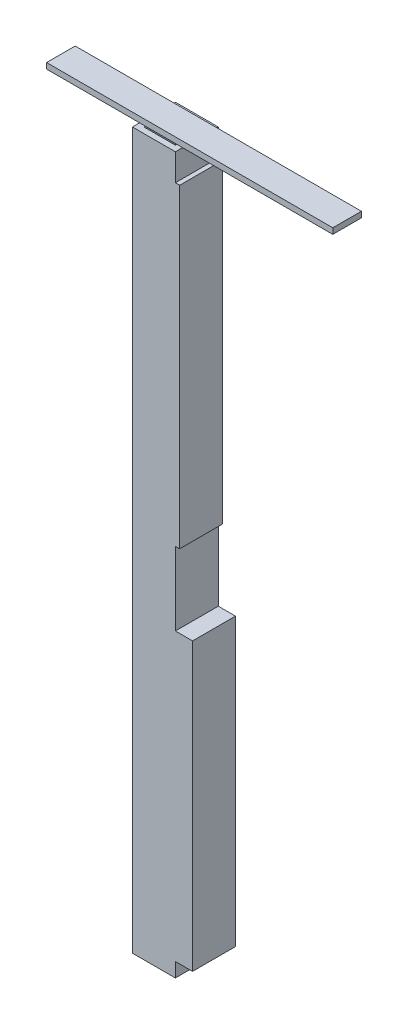
SolidWorks part; units mm, degrees
ref_plane "Front Plane" through (0, 0, 0) normal (0, 0, 1) x (1, 0, 0)
ref_plane "Top Plane" through (0, 0, 0) normal (0, 1, 0) x (1, 0, 0)
ref_plane "Right Plane" through (0, 0, 0) normal (1, 0, 0) x (0, 0, -1)
sketch "Sketch1" plane through (0, 0, 0) normal (0, 1, 0) x (1, 0, 0)
  line L1 (-15, 15) -> (15, 15)
  line L2 (-15, 15) -> (-15, -15)
  line L3 (-15, -15) -> (15, -15)
  line L4 (15, 15) -> (15, -15)
  dimension "D1" = 30
  dimension "D2" = 30
  dimension "D3" = 15
  dimension "D4" = 15
extrude "Extrude1" add sketch "Sketch1" along normal blind 500
sketch "Sketch2" plane through (0, 500, 0) normal (0, 1, 0) x (1, 0, 0)
  line L0 (15, 15) -> (-15, 15) construction
  line L1 (-11, 11) -> (11, 11)
  line L2 (-11, 11) -> (-11, -11)
  line L3 (-11, -11) -> (11, -11)
  line L4 (11, 11) -> (11, -11)
  line L5 (15, -15) -> (15, 15) construction
  line L6 (-15, -15) -> (15, -15) construction
  line L7 (-15, 15) -> (-15, -15) construction
  dimension "D1" = 4
  dimension "D2" = 4
  dimension "D3" = 4
  dimension "D4" = 4
extrude "Cut-Extrude1" cut sketch "Sketch2" against normal blind 500
sketch "Sketch3" plane through (0, 500, 0) normal (0, 1, 0) x (1, 0, 0)
  line L1 (-80, 10) -> (120, 10)
  line L2 (-80, 10) -> (-80, -10)
  line L3 (-80, -10) -> (120, -10)
  line L4 (120, 10) -> (120, -10)
  dimension "D1" = 20
  dimension "D2" = 10
  dimension "D3" = 80
  dimension "D4" = 120
extrude "Extrude2" add sketch "Sketch3" along normal blind 4
sketch "Sketch4" plane through (15, 0, 0) normal (1, 0, 0) x (0, 0, -1)
  line L0 (-15, 500) -> (-15, 0) construction
  line L1 (-15, 210) -> (15, 210)
  line L2 (-15, 210) -> (-15, 10)
  line L3 (-15, 10) -> (15, 10)
  line L4 (15, 210) -> (15, 10)
  line L5 (15, 500) -> (15, 0) construction
  line L6 (-15, 0) -> (15, 0) construction
  dimension "D1" = 200
  dimension "D2" = 30
  dimension "D3" = 10
extrude "Extrude3" add sketch "Sketch4" along normal blind 12
sketch "Sketch6" plane through (15, 0, 0) normal (1, 0, 0) x (0, 0, -1)
  line L0 (-15, 500) -> (-15, 210) construction
  line L1 (-15, 481.2385) -> (15, 481.2385)
  line L2 (-15, 481.2385) -> (-15, 261.2385)
  line L3 (-15, 261.2385) -> (15, 261.2385)
  line L4 (15, 481.2385) -> (15, 261.2385)
  line L5 (15, 500) -> (15, 210) construction
  dimension "D1" = 220
extrude "Extrude4" add sketch "Sketch6" along normal blind 3
